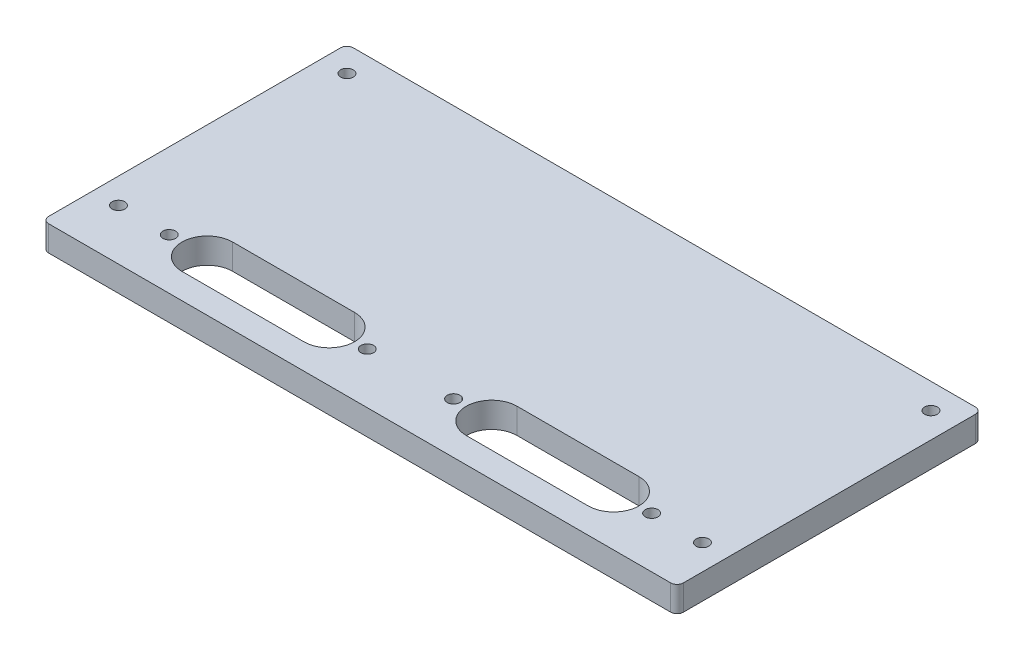
SolidWorks part; units mm, degrees
ref_plane "Front Plane" through (0, 0, 0) normal (0, 0, 1) x (1, 0, 0)
ref_plane "Top Plane" through (0, 0, 0) normal (0, 1, 0) x (1, 0, 0)
ref_plane "Right Plane" through (0, 0, 0) normal (1, 0, 0) x (0, 0, -1)
sketch "Sketch1" plane through (0, 0, 0) normal (0, 1, 0) x (1, 0, 0)
  line L0 (57.15, 25.4) -> (118.11, 25.4) construction
  line L1 (0, 0) -> (317.5, 0)
  line L2 (0, 0) -> (0, 152.4)
  line L3 (0, 152.4) -> (317.5, 152.4)
  line L4 (317.5, 0) -> (317.5, 152.4)
  line L5 (57.15, 38.1) -> (118.11, 38.1)
  line L6 (57.15, 12.7) -> (118.11, 12.7)
  line L7 (0, 25.4) -> (317.5, 25.4) construction
  line L8 (158.75, 152.4) -> (158.75, 0) construction
  line L9 (260.35, 25.4) -> (199.39, 25.4) construction
  line L10 (260.35, 38.1) -> (199.39, 38.1)
  line L11 (260.35, 12.7) -> (199.39, 12.7)
  circle A0 centre (12.7, 25.4) radius 3.175
  circle A1 centre (12.7, 139.7) radius 3.175
  circle A2 centre (304.8, 139.7) radius 3.175
  circle A3 centre (304.8, 25.4) radius 3.175
  arc A4 (57.15, 38.1) -> (57.15, 12.7) centre (57.15, 25.4) ccw
  arc A5 (118.11, 12.7) -> (118.11, 38.1) centre (118.11, 25.4) ccw
  circle A6 centre (38.1, 25.4) radius 3.175
  circle A7 centre (137.16, 25.4) radius 3.175
  arc A8 (260.35, 38.1) -> (260.35, 12.7) centre (260.35, 25.4) cw
  arc A9 (199.39, 12.7) -> (199.39, 38.1) centre (199.39, 25.4) cw
  circle A10 centre (180.34, 25.4) radius 3.175
  circle A11 centre (279.4, 25.4) radius 3.175
  point P15 (87.63, 25.4)
  point P28 (229.87, 25.4)
  dimension "D3" = 6.35
  dimension "D6" = 6.35
  dimension "D9" = 6.35
  dimension "D12" = 6.35
  dimension "D17" = 6.35
  dimension "D19" = 6.35
  dimension "D1" = 317.5
  dimension "D2" = 152.4
  dimension "D4" = 25.4
  dimension "D5" = 12.7
  dimension "D7" = 12.7
  dimension "D8" = 12.7
  dimension "D10" = 12.7
  dimension "D11" = 12.7
  dimension "D13" = 12.7
  dimension "D14" = 25.4
  dimension "D15" = 60.96
  dimension "D16" = 25.4
  dimension "D18" = 19.05
  dimension "D20" = 19.05
  dimension "D21" = 38.1
  dimension "D22" = 25.4
extrude "Boss-Extrude1" add sketch "Sketch1" along normal blind 12.7
fillet "Fillet1" radius 3.175 4 edges at (0, 6.35, -152.4) (0, 6.35, 0) (317.5, 6.35, -152.4) (317.5, 6.35, 0)
